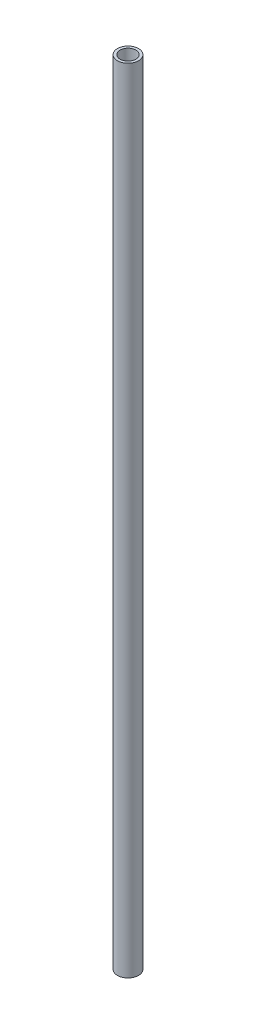
SolidWorks part; units mm, degrees
ref_plane "Front Plane" through (0, 0, 0) normal (0, 0, 1) x (1, 0, 0)
ref_plane "Top Plane" through (0, 0, 0) normal (0, 1, 0) x (1, 0, 0)
ref_plane "Right Plane" through (0, 0, 0) normal (1, 0, 0) x (0, 0, -1)
sketch "Sketch1" plane through (0, 0, 0) normal (0, 0, 1) x (1, 0, 0)
  line L0 (0, 0) -> (0, 300)
  point P6 (0, 300)
  dimension "D1" = 300
sketch "Sketch2" plane through (0, 0, 0) normal (0, 1, 0) x (1, 0, 0)
  circle A0 centre (0, 0) radius 4
  circle A1 centre (0, 0) radius 3
  dimension "D1" = 6
  dimension "D2" = 8
sweep "Sweep1" add profiles "Sketch2" path "Sketch1"
